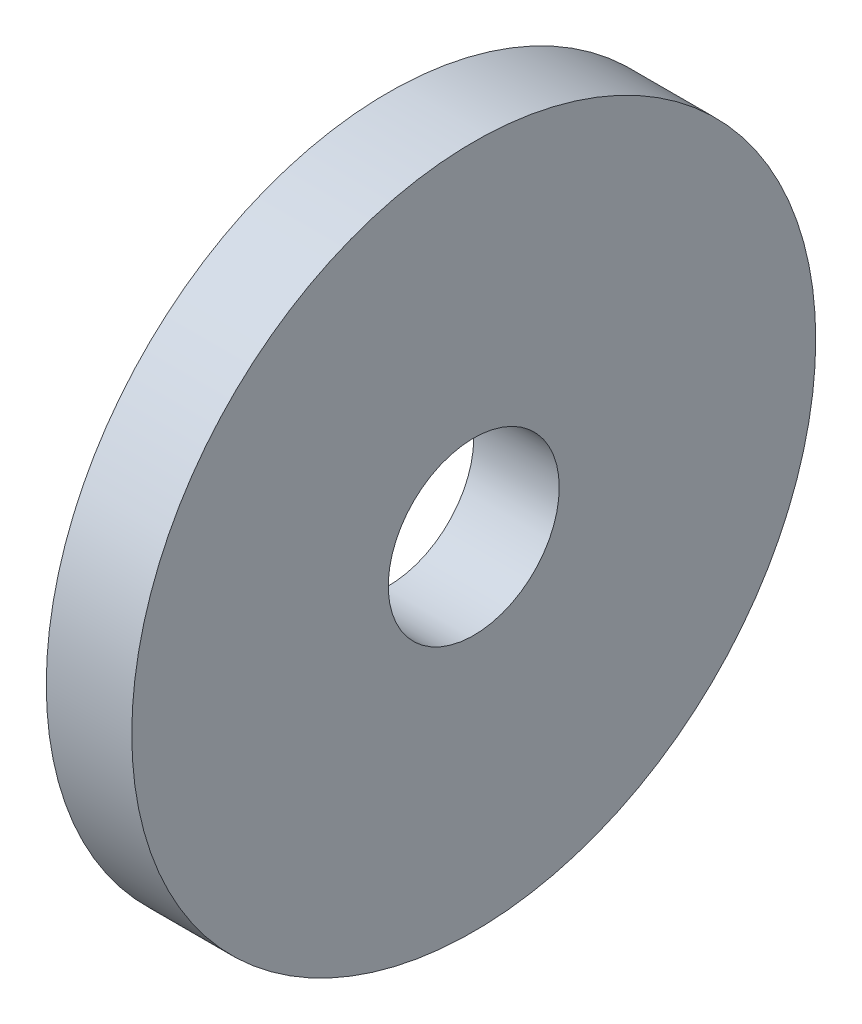
SolidWorks part; units mm, degrees
ref_plane "Front Plane" through (0, 0, 0) normal (0, 0, 1) x (1, 0, 0)
ref_plane "Top Plane" through (0, 0, 0) normal (0, 1, 0) x (1, 0, 0)
ref_plane "Right Plane" through (0, 0, 0) normal (1, 0, 0) x (0, 0, -1)
sketch "Sketch1" plane through (0, 0, 0) normal (1, 0, 0) x (0, 0, -1)
  circle A0 centre (0, 0) radius 12.7
  circle A1 centre (0, 0) radius 3.175
  dimension "D1" = 25.4
  dimension "D2" = 6.35
extrude "Boss-Extrude1" add sketch "Sketch1" along normal blind 3.175
